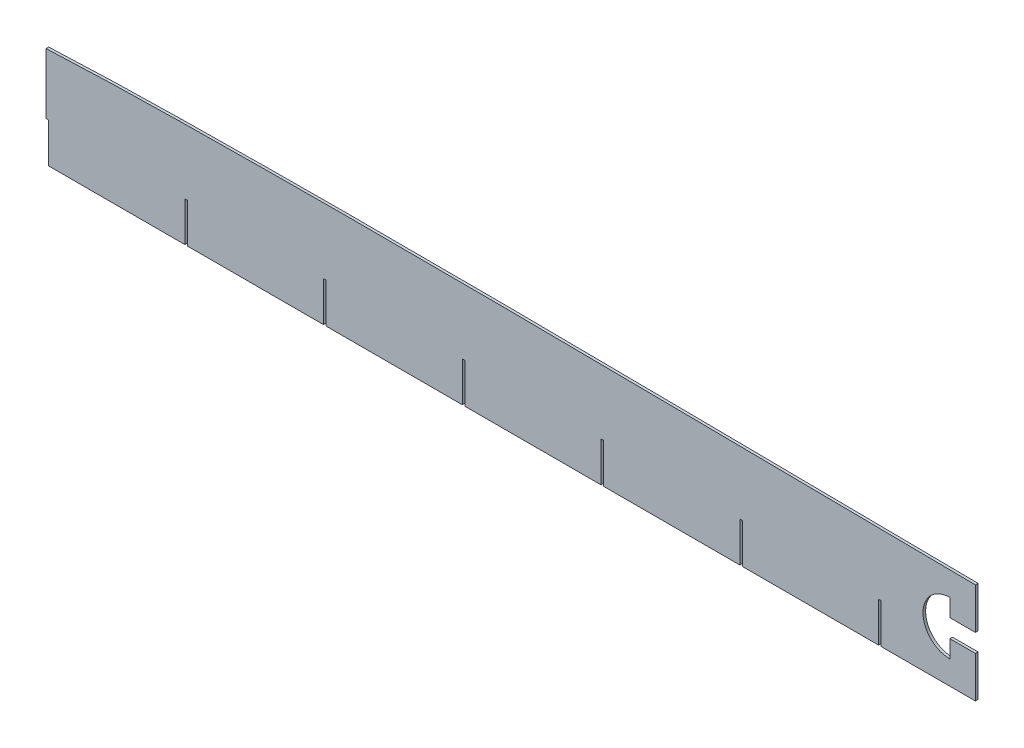
SolidWorks part; units mm, degrees
ref_plane "Front Plane" through (0, 0, 0) normal (0, 0, 1) x (1, 0, 0)
ref_plane "Top Plane" through (0, 0, 0) normal (0, 1, 0) x (1, 0, 0)
ref_plane "Right Plane" through (0, 0, 0) normal (1, 0, 0) x (0, 0, -1)
sketch "Model" plane through (0, 0, 0) normal (0, 0, 1) x (1, 0, 0)
  line L0 (1159.8, 315.6827) -> (1159.8, 268.4527)
  line L1 (94.901, 245.9797) -> (94.901, 315.4413)
  line L2 (97.901, 245.9797) -> (94.901, 245.9797)
  line L3 (97.901, 200.4227) -> (97.901, 245.9797)
  line L4 (97.901, 200.4227) -> (253.901, 200.4227)
  line L5 (253.901, 245.9797) -> (253.901, 200.4227)
  line L6 (256.901, 245.9797) -> (253.901, 245.9797)
  line L7 (256.901, 200.4227) -> (256.901, 245.9797)
  line L8 (256.901, 200.4227) -> (412.901, 200.4227)
  line L9 (412.901, 245.9797) -> (412.901, 200.4227)
  line L10 (415.901, 245.9797) -> (412.901, 245.9797)
  line L11 (415.901, 200.4227) -> (415.901, 245.9797)
  line L12 (415.901, 200.4227) -> (571.901, 200.4227)
  line L13 (571.901, 245.9797) -> (571.901, 200.4227)
  line L14 (574.901, 245.9797) -> (571.901, 245.9797)
  line L15 (574.901, 200.4227) -> (574.901, 245.9797)
  line L16 (574.901, 200.4227) -> (730.901, 200.4227)
  line L17 (730.901, 245.9797) -> (730.901, 200.4227)
  line L18 (733.901, 245.9797) -> (730.901, 245.9797)
  line L19 (733.901, 200.4227) -> (733.901, 245.9797)
  line L20 (733.901, 200.4227) -> (889.901, 200.4227)
  line L21 (889.901, 245.9797) -> (889.901, 200.4227)
  line L22 (892.901, 245.9797) -> (889.901, 245.9797)
  line L23 (892.901, 200.4227) -> (892.901, 245.9797)
  line L24 (892.901, 200.4227) -> (1048.901, 200.4227)
  line L25 (1048.901, 245.9797) -> (1048.901, 200.4227)
  line L26 (1051.901, 245.9797) -> (1048.901, 245.9797)
  line L27 (1051.901, 200.4227) -> (1051.901, 245.9797)
  line L28 (1051.901, 200.4227) -> (1159.8, 200.4227)
  line L29 (1159.8, 247.6527) -> (1159.8, 200.4227)
  line L30 (1130.6, 247.6527) -> (1159.8, 247.6527)
  line L31 (1130.6, 247.6527) -> (1130.6, 227.6553)
  line L32 (1130.6, 288.45) -> (1130.6, 268.4527)
  line L33 (1130.6, 268.4527) -> (1159.8, 268.4527)
  arc A0 (1130.6, 288.45) -> (1130.6, 227.6553) centre (1130.2, 258.0527) ccw
  spline S0 degree 3 poles (1159.8, 315.6827) (855.6073, 318.0332) (551.3397, 324.4276) (247.237, 319.8883) knots 0 0 0 0 1 1 1 1
  spline S1 degree 3 poles (247.2299, 319.8882) (247.2323, 319.8882) (247.2347, 319.8883) (247.237, 319.8883) knots 0.554606 0.554606 0.554606 0.554606 0.554611 0.554611 0.554611 0.554611
  spline S2 degree 3 poles (247.2299, 319.8882) (196.4384, 319.13) (145.6586, 317.8127) (94.901, 315.4413) knots 0 0 0 0 1 1 1 1
extrude "Boss-Extrude1" add sketch "Model" along normal blind 3
